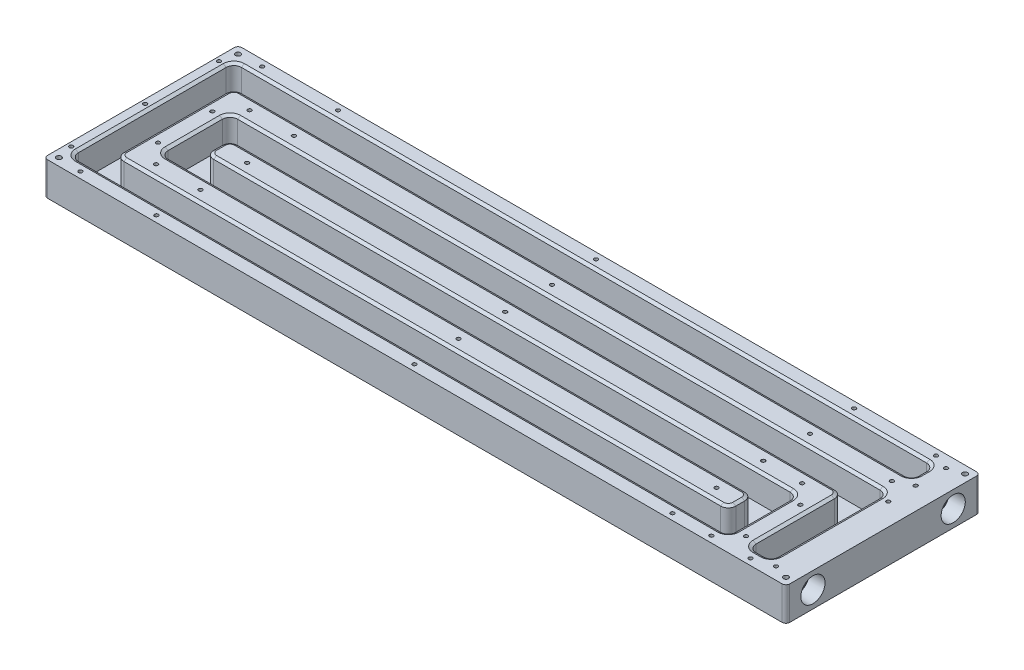
SolidWorks part; units mm, degrees
material "6061 Alloy"
ref_plane "Front Plane" through (0, 0, 0) normal (0, 0, 1) x (1, 0, 0)
ref_plane "Top Plane" through (0, 0, 0) normal (0, 1, 0) x (1, 0, 0)
ref_plane "Right Plane" through (0, 0, 0) normal (1, 0, 0) x (0, 0, -1)
sketch "Sketch1" plane through (0, 0, 0) normal (0, 1, 0) x (1, 0, 0)
  line L1 (-244.475, 67) -> (244.475, 67)
  line L2 (-244.475, 67) -> (-244.475, -67)
  line L3 (-244.475, -67) -> (244.475, -67)
  line L4 (244.475, 67) -> (244.475, -67)
  line L5 (-244.475, 67) -> (244.475, -67) construction
  line L6 (-244.475, -67) -> (244.475, 67) construction
  point P0 (0, 0)
  dimension "D1" = 134
  dimension "D2" = 488.95
extrude "Boss-Extrude1" add sketch "Sketch1" along normal blind 22
hole_wizard "3/8 NPT Tapped Hole1" positions "Sketch2" profile "Sketch3" size "3/8" standard "ANSI Inch"
sketch "Sketch2" plane through (244.475, 0, 0) normal (1, 0, 0) x (0, 0, -1)
  line L0 (46.2, 11) -> (-46.2, 11) construction
  line L2 (-67, 22) -> (-67, 0) construction
  point P0 (-46.2, 11)
  point P2 (46.2, 11)
  point P8 (0, 11)
  point P12 (-67, 11)
  dimension "D1" = 92.4
sketch "Sketch3" plane through (244.475, 11, 46.2) normal (0, 1, 0) x (0, 0, -1)
  line L0 (0, 0) -> (0, 21.6686)
  line L1 (7.1374, 17.38) -> (0, 21.6686)
  line L2 (-7.1374, 17.38) -> (0, 21.6686) construction
  line L3 (7.1374, 17.38) -> (7.1374, 10.33)
  line L4 (7.1374, 10.33) -> (7.6537, 10.33)
  line L5 (7.6537, 10.33) -> (7.963, 0)
  line L6 (-7.6537, 10.33) -> (-7.963, 0) construction
  line L7 (7.963, 0) -> (0, 0)
  line L8 (0, -6.35) -> (0, 107.95) construction
  line L11 (-7.1374, 10.33) -> (-7.6537, 10.33) construction
  dimension "Tap Drill Dia." = 14.2748
  dimension "Tap Drill Depth" = 17.38
  dimension "Thread Dia." = 15.9261
  dimension "Thread Angle" = 3.43
  dimension "Thread Depth" = 10.33
  dimension "Drill Angle" = 118
cosmetic thread "Hole Thread1" parameters "D1"=10.33, "D2"=17.145
cosmetic thread "Hole Thread2" parameters "D1"=10.33, "D2"=17.145
sketch "Sketch4" plane through (0, 22, 0) normal (0, 1, 0) x (1, 0, 0)
  line L0 (-244.475, 67) -> (-244.475, -67) construction
  line L1 (224.475, 53.7) -> (-236.975, 53.7)
  line L2 (224.475, 53.7) -> (224.475, 38.7)
  line L3 (224.475, 38.7) -> (-236.975, 38.7)
  line L4 (-236.975, 53.7) -> (-236.975, 38.7)
  line L5 (244.475, 67) -> (-244.475, 67) construction
  line L6 (244.475, -67) -> (244.475, 67) construction
  dimension "D1" = 7.5
  dimension "D2" = 13.3
  dimension "D3" = 20
  dimension "D4" = 15
extrude "Cut-Extrude1" cut sketch "Sketch4" against normal blind 18
pattern_linear "LPattern1" count 4 spacing 30.8 along (0, 0, 1) of "Cut-Extrude1"
sketch "Sketch5" plane through (0, 22, 0) normal (0, 1, 0) x (1, 0, 0)
  line L0 (224.475, 22.9) -> (-236.975, 22.9) construction
  line L1 (-236.975, -22.9) -> (-208.675, -22.9)
  line L2 (-236.975, -22.9) -> (-236.975, 22.9)
  line L3 (-236.975, 22.9) -> (-208.675, 22.9)
  line L4 (-208.675, -22.9) -> (-208.675, 22.9)
  dimension "D1" = 28.3
extrude "Boss-Extrude2" add sketch "Sketch5" against normal up to next
sketch "Sketch6" plane through (0, 22, 0) normal (0, 1, 0) x (1, 0, 0)
  line L0 (224.475, -7.9) -> (-208.675, -7.9) construction
  line L1 (224.475, -53.7) -> (196.175, -53.7)
  line L2 (224.475, -53.7) -> (224.475, -7.9)
  line L3 (224.475, -7.9) -> (196.175, -7.9)
  line L4 (196.175, -53.7) -> (196.175, -7.9)
  dimension "D1" = 28.3
extrude "Boss-Extrude3" add sketch "Sketch6" against normal up to next
sketch "Sketch7" plane through (0, 22, 0) normal (0, 1, 0) x (1, 0, 0)
  line L0 (-208.675, 7.9) -> (224.475, 7.9) construction
  line L1 (209.475, 7.9) -> (224.475, 7.9)
  line L2 (209.475, 7.9) -> (209.475, -53.7)
  line L3 (209.475, -53.7) -> (224.475, -53.7)
  line L4 (224.475, 7.9) -> (224.475, -53.7)
  line L5 (-244.475, -67) -> (244.475, -67) construction
  line L6 (196.175, -38.7) -> (196.175, -53.7) construction
  dimension "D1" = 15
  dimension "D2" = 13.3
  dimension "D3" = 13.3
extrude "Cut-Extrude2" cut sketch "Sketch7" against normal blind 18
sketch "Sketch8" plane through (0, 22, 0) normal (0, 1, 0) x (1, 0, 0)
  line L0 (-208.675, -22.9) -> (196.175, -22.9) construction
  line L1 (196.175, -38.7) -> (181.175, -38.7)
  line L2 (196.175, -38.7) -> (196.175, -22.9)
  line L3 (196.175, -22.9) -> (181.175, -22.9)
  line L4 (181.175, -38.7) -> (181.175, -22.9)
  dimension "D1" = 15
extrude "Cut-Extrude3" cut sketch "Sketch8" against normal blind 18
sketch "Sketch9" plane through (0, 22, 0) normal (0, 1, 0) x (1, 0, 0)
  line L0 (-236.975, 38.7) -> (224.475, 38.7) construction
  line L1 (-236.975, -38.7) -> (-221.975, -38.7)
  line L2 (-236.975, -38.7) -> (-236.975, 38.7)
  line L3 (-236.975, 38.7) -> (-221.975, 38.7)
  line L4 (-221.975, -38.7) -> (-221.975, 38.7)
  dimension "D1" = 15
extrude "Cut-Extrude4" cut sketch "Sketch9" against normal blind 18
sketch "Sketch10" plane through (0, 22, 0) normal (0, 1, 0) x (1, 0, 0)
  line L0 (-208.675, 7.9) -> (209.475, 7.9) construction
  line L1 (-208.675, -7.9) -> (-193.675, -7.9)
  line L2 (-208.675, -7.9) -> (-208.675, 7.9)
  line L3 (-208.675, 7.9) -> (-193.675, 7.9)
  line L4 (-193.675, -7.9) -> (-193.675, 7.9)
  dimension "D1" = 15
extrude "Cut-Extrude5" cut sketch "Sketch10" against normal blind 18
fillet "Fillet1" radius 5 18 edges at (196.175, 13, 7.9) (181.175, 13, 22.9) (181.175, 13, 38.7) (196.175, 13, 53.7) (209.475, 13, 53.7) (224.475, 13, 53.7) (209.475, 13, -7.9) (-208.675, 13, -22.9) (224.475, 13, -22.9) (224.475, 13, -38.7) (224.475, 13, -53.7) (-221.975, 13, -38.7) (-221.975, 13, 38.7) (-236.975, 13, 53.7) (-193.675, 13, -7.9) (-193.675, 13, 7.9) (-208.675, 13, 22.9) (-236.975, 13, -53.7)
chamfer "Chamfer1" distance 2 angle 30 36 edges at (1.25, 22, 7.9) (196.175, 22, 30.8) (181.175, 22, 30.8) (-13.75, 22, 22.9) (-208.675, 22, 0) (7.9, 22, -22.9) (224.475, 22, 15.4) (216.975, 22, 53.7) (209.475, 22, 22.9) (7.9, 22, -7.9) (-193.675, 22, 0) (-20.4, 22, 53.7) (-236.975, 22, 0) (-6.25, 22, -53.7) (224.475, 22, -46.2) (1.25, 22, -38.7) (-221.975, 22, 0) (-20.4, 22, 38.7) (-192.2105, 22, 6.4355) (-192.2105, 22, -6.4355) (-220.5105, 22, 37.2355) (-220.5105, 22, -37.2355) (208.0105, 22, -6.4355) (179.7105, 22, 37.2355) (179.7105, 22, 24.3645) (194.7105, 22, 9.3645) (194.7105, 22, 52.2355) (210.9395, 22, 52.2355) (223.0105, 22, 52.2355) (223.0105, 22, -21.4355) (223.0105, 22, -40.1645) (223.0105, 22, -52.2355) (-235.5105, 22, 52.2355) (-207.2105, 22, 21.4355) (-207.2105, 22, -21.4355) (-235.5105, 22, -52.2355)
hole_wizard "M3x0.5 Tapped Hole5" positions "Sketch27" profile "Sketch28" tap size "M3x0.5" standard "ANSI Metric"
sketch "Sketch27" plane through (0, 0, 0) normal (0, -1, 0) x (-1, 0, 0)
  line L0 (191.975, 32.7657) -> (191.975, -28.8343) construction
  line L3 (244.475, 67) -> (244.475, -67) construction
  point P0 (191.975, -28.8343)
  point P2 (191.975, 32.7657)
  dimension "D1" = 61.6
  dimension "D2" = 52.5
sketch "Sketch28" plane through (-191.975, 0, 28.8343) normal (1, 0, 0) x (0, 0, -1)
  line L0 (0, 0) -> (0, 9.2511)
  line L1 (0, 9.2511) -> (1.25, 8.5)
  line L2 (1.25, 8.5) -> (1.25, 0)
  line L5 (1.25, 0) -> (0, 0)
  line L10 (0, 9.2511) -> (-1.25, 8.5) construction
  line L11 (0, -6.35) -> (0, 107.95) construction
  dimension "Tap Drill Dia." = 2.5
  dimension "Tap Drill Depth" = 8.5
  dimension "Drill Angle" = 118
sketch "Sketch15" plane through (0, 22, 0) normal (0, 1, 0) x (1, 0, 0)
  line L0 (-244.475, 67) -> (-244.475, -67) construction
  line L1 (244.475, -67) -> (-244.475, -67)
  line L2 (244.475, -67) -> (244.475, -64)
  line L3 (244.475, -64) -> (-244.475, -64)
  line L4 (-244.475, -67) -> (-244.475, -64)
  dimension "D1" = 3
extrude "Cut-Extrude6" cut sketch "Sketch15" against normal through all
sketch "Sketch16" plane through (0, 22, 0) normal (0, 1, 0) x (1, 0, 0)
  line L0 (-244.475, 67) -> (-244.475, -64) construction
  line L1 (244.475, 67) -> (-244.475, 67)
  line L2 (244.475, 67) -> (244.475, 64)
  line L3 (244.475, 64) -> (-244.475, 64)
  line L4 (-244.475, 67) -> (-244.475, 64)
  dimension "D1" = 3
extrude "Cut-Extrude7" cut sketch "Sketch16" against normal through all
fillet "Fillet2" radius 2.5 4 edges at (-244.475, 11, 64) (-244.475, 11, -64) (244.475, 11, 64) (244.475, 11, -64)
hole_wizard "M4x0.7 Tapped Hole1" positions "Sketch22" profile "Sketch23" tap size "M4x0.7" standard "ANSI Metric"
sketch "Sketch22" plane through (0, 22, 0) normal (0, 1, 0) x (1, 0, 0)
  line L0 (-239.475, -59) -> (-239.475, 59) construction
  line L1 (-239.475, 59) -> (239.475, 59) construction
  line L2 (239.475, 59) -> (239.475, -59) construction
  line L3 (239.475, -59) -> (-239.475, -59) construction
  line L6 (241.975, -64) -> (-241.975, -64) construction
  line L7 (-244.475, 61.5) -> (-244.475, -61.5) construction
  line L8 (-241.975, 64) -> (241.975, 64) construction
  line L9 (244.475, -61.5) -> (244.475, 61.5) construction
  point P0 (239.475, -59)
  point P2 (239.475, 59)
  point P4 (-239.475, 59)
  point P6 (-239.475, -59)
  dimension "D1" = 5
  dimension "D2" = 5
  dimension "D3" = 5
  dimension "D4" = 5
sketch "Sketch23" plane through (239.475, 22, 59) normal (1, 0, 0) x (0, 0, 1)
  line L0 (0, 0) -> (0, 12.4914)
  line L1 (0, 12.4914) -> (1.65, 11.5)
  line L2 (1.65, 11.5) -> (1.65, 0)
  line L5 (1.65, 0) -> (0, 0)
  line L10 (0, 12.4914) -> (-1.65, 11.5) construction
  line L11 (0, -6.35) -> (0, 107.95) construction
  dimension "Tap Drill Dia." = 3.3
  dimension "Tap Drill Depth" = 11.5
  dimension "Drill Angle" = 118
hole_wizard "M3x0.5 Tapped Hole1" positions "Sketch11" profile "Sketch12" tap size "M3x0.5" standard "ANSI Metric"
sketch "Sketch11" plane through (0, 22, 0) normal (0, 1, 0) x (1, 0, 0)
  line L2 (-244.475, 61.5) -> (-244.475, -61.5) construction
  line L3 (-174.475, 36.7) -> (-174.475, 24.9) construction
  line L4 (219.475, 36.7) -> (-216.975, 36.7) construction
  line L5 (-203.675, 24.9) -> (219.475, 24.9) construction
  line L8 (-174.475, -24.9) -> (-174.475, -36.7) construction
  line L9 (176.175, -24.9) -> (-203.675, -24.9) construction
  line L10 (-216.975, -36.7) -> (176.175, -36.7) construction
  line L21 (-174.475, -55.7) -> (-174.475, -64) construction
  line L22 (191.175, -55.7) -> (-231.975, -55.7) construction
  line L23 (241.975, -64) -> (-241.975, -64) construction
  line L26 (-174.475, -5.9) -> (-174.475, 5.9) construction
  line L27 (-188.675, -5.9) -> (191.175, -5.9) construction
  line L28 (204.475, 5.9) -> (-188.675, 5.9) construction
  line L31 (-174.475, 55.7) -> (-174.475, 64) construction
  line L32 (-231.975, 55.7) -> (219.475, 55.7) construction
  line L33 (-241.975, 64) -> (241.975, 64) construction
  point P0 (-174.475, 0)
  point P11 (-174.475, -30.8)
  point P13 (-174.475, -59.85)
  point P15 (-174.475, 30.8)
  point P17 (-174.475, 59.85)
  point P48 (-174.475, -30.8)
  point P49 (-174.475, 30.8)
  point P72 (-174.475, -59.85)
  point P91 (-174.475, 59.85)
  dimension "D2" = 70
sketch "Sketch12" plane through (-174.475, 22, 0) normal (1, 0, 0) x (0, 0, 1)
  line L0 (0, 0) -> (0, 9.2511)
  line L1 (0, 9.2511) -> (1.25, 8.5)
  line L2 (1.25, 8.5) -> (1.25, 0)
  line L5 (1.25, 0) -> (0, 0)
  line L10 (0, 9.2511) -> (-1.25, 8.5) construction
  line L11 (0, -6.35) -> (0, 107.95) construction
  dimension "Tap Drill Dia." = 2.5
  dimension "Tap Drill Depth" = 8.5
  dimension "Drill Angle" = 118
pattern_linear "LPattern3" count 3 spacing 170 along (1, 0, 0) of "M3x0.5 Tapped Hole1"
hole_wizard "M3x0.5 Tapped Hole2" positions "Sketch18" profile "Sketch19" tap size "M3x0.5" standard "ANSI Metric"
sketch "Sketch18" plane through (0, 22, 0) normal (0, 1, 0) x (1, 0, 0)
  line L0 (191.175, -55.7) -> (191.175, -64) construction
  line L1 (241.975, -64) -> (-241.975, -64) construction
  line L4 (207.475, -48.7) -> (198.175, -48.7) construction
  line L8 (207.475, -48.7) -> (207.475, 2.9) construction
  line L12 (198.175, -12.9) -> (207.475, -12.9) construction
  line L15 (191.175, -5.9) -> (191.175, 5.9) construction
  line L16 (204.475, 5.9) -> (-188.675, 5.9) construction
  point P2 (191.175, 0)
  point P4 (202.825, -12.9)
  point P6 (202.825, -48.7)
  point P8 (191.175, -59.85)
  point P51 (202.825, -12.9)
  point P53 (202.825, -48.7)
  point P54 (191.175, -59.85)
sketch "Sketch19" plane through (191.175, 22, 0) normal (1, 0, 0) x (0, 0, 1)
  line L0 (0, 0) -> (0, 10.7511)
  line L1 (0, 10.7511) -> (1.25, 10)
  line L2 (1.25, 10) -> (1.25, 0)
  line L5 (1.25, 0) -> (0, 0)
  line L10 (0, 10.7511) -> (-1.25, 10) construction
  line L11 (0, -6.35) -> (0, 107.95) construction
  dimension "Tap Drill Dia." = 2.5
  dimension "Tap Drill Depth" = 10
  dimension "Drill Angle" = 118
hole_wizard "M3x0.5 Tapped Hole3" positions "Sketch20" profile "Sketch21" tap size "M3x0.5" standard "ANSI Metric"
sketch "Sketch20" plane through (0, 22, 0) normal (0, 1, 0) x (1, 0, 0)
  line L0 (229.975, -56) -> (229.975, 56) construction
  line L2 (226.475, 17.9) -> (226.475, -48.7) construction
  line L3 (219.475, 24.9) -> (219.475, 36.7) construction
  line L4 (-203.675, 24.9) -> (219.475, 24.9) construction
  line L5 (219.475, 36.7) -> (-216.975, 36.7) construction
  line L8 (219.475, 55.7) -> (219.475, 64) construction
  line L9 (-231.975, 55.7) -> (219.475, 55.7) construction
  line L10 (-241.975, 64) -> (241.975, 64) construction
  line L13 (216.975, -55.7) -> (216.975, -64) construction
  line L14 (219.475, -55.7) -> (214.475, -55.7) construction
  line L15 (241.975, -64) -> (-241.975, -64) construction
  line L18 (202.825, -12.9) -> (229.975, -12.9) construction
  line L20 (229.975, -56) -> (229.975, -36) construction
  point P0 (219.475, 59.85)
  point P2 (219.475, 30.8)
  point P4 (229.975, 36)
  point P6 (229.975, 56)
  point P8 (229.975, 17.9)
  point P14 (229.975, -56)
  point P16 (216.975, -59.85)
  point P52 (216.975, -59.85)
  point P53 (216.975, -55.7)
  point P54 (219.475, 30.8)
  point P55 (219.475, 59.85)
  dimension "D1" = 3.5
  dimension "D3" = 20
  dimension "D4" = 8
  dimension "D5" = 8
sketch "Sketch21" plane through (219.475, 22, -59.85) normal (1, 0, 0) x (0, 0, 1)
  line L0 (0, 0) -> (0, 9.2511)
  line L1 (0, 9.2511) -> (1.25, 8.5)
  line L2 (1.25, 8.5) -> (1.25, 0)
  line L5 (1.25, 0) -> (0, 0)
  line L10 (0, 9.2511) -> (-1.25, 8.5) construction
  line L11 (0, -6.35) -> (0, 107.95) construction
  dimension "Tap Drill Dia." = 2.5
  dimension "Tap Drill Depth" = 8.5
  dimension "Drill Angle" = 118
hole_wizard "M3x0.5 Tapped Hole4" positions "Sketch24" profile "Sketch25" tap size "M3x0.5" standard "ANSI Metric"
sketch "Sketch24" plane through (0, 22, 0) normal (0, 1, 0) x (1, 0, 0)
  line L0 (-210.675, -17.9) -> (-219.975, -17.9) construction
  line L1 (-219.975, 33.7) -> (-219.975, -33.7) construction
  line L4 (-210.675, 0) -> (-219.975, 0) construction
  line L5 (-210.675, -17.9) -> (-210.675, 17.9) construction
  line L8 (-210.675, 17.9) -> (-219.975, 17.9) construction
  line L11 (-203.675, 24.9) -> (-203.675, 36.7) construction
  line L12 (219.475, 36.7) -> (-216.975, 36.7) construction
  line L15 (-203.675, -24.9) -> (-203.675, -36.7) construction
  line L16 (-216.975, -36.7) -> (176.175, -36.7) construction
  line L19 (-238.975, -48.7) -> (-244.475, -48.7) construction
  line L20 (-244.475, 61.5) -> (-244.475, -61.5) construction
  line L23 (-238.975, 0) -> (-244.475, 0) construction
  line L24 (-238.975, -48.7) -> (-238.975, 48.7) construction
  line L27 (-238.975, 48.7) -> (-244.475, 48.7) construction
  line L30 (-224.475, 55.7) -> (-224.475, 64) construction
  line L31 (-231.975, 55.7) -> (219.475, 55.7) construction
  line L32 (-241.975, 64) -> (241.975, 64) construction
  line L35 (-224.475, -55.7) -> (-224.475, -64) construction
  line L36 (191.175, -55.7) -> (-231.975, -55.7) construction
  line L37 (241.975, -64) -> (-241.975, -64) construction
  arc A0 (-203.675, 24.9) -> (-210.675, 17.9) centre (-203.675, 17.9) ccw construction
  point P2 (-215.325, -17.9)
  point P4 (-215.325, 17.9)
  point P6 (-203.675, 30.8)
  point P8 (-203.675, -30.8)
  point P10 (-224.475, -59.85)
  point P12 (-241.725, -48.7)
  point P14 (-241.725, 0)
  point P16 (-241.725, 48.7)
  point P18 (-224.475, 59.85)
  point P100 (-241.725, -48.7)
  point P101 (-224.475, -59.85)
  point P102 (-203.675, -30.8)
  point P103 (-215.325, -17.9)
  point P105 (-241.725, 0)
  point P106 (-215.325, 17.9)
  point P107 (-203.675, 30.8)
  point P108 (-224.475, 59.85)
  point P109 (-241.725, 48.7)
  dimension "D1" = 20
  dimension "D2" = 20
sketch "Sketch25" plane through (-215.325, 22, 17.9) normal (1, 0, 0) x (0, 0, 1)
  line L0 (0, 0) -> (0, 9.2511)
  line L1 (0, 9.2511) -> (1.25, 8.5)
  line L2 (1.25, 8.5) -> (1.25, 0)
  line L5 (1.25, 0) -> (0, 0)
  line L10 (0, 9.2511) -> (-1.25, 8.5) construction
  line L11 (0, -6.35) -> (0, 107.95) construction
  dimension "Tap Drill Dia." = 2.5
  dimension "Tap Drill Depth" = 8.5
  dimension "Drill Angle" = 118
pattern_linear "LPattern4" count 5 spacing 97.5 along (1, 0, 0) of "M3x0.5 Tapped Hole5"
